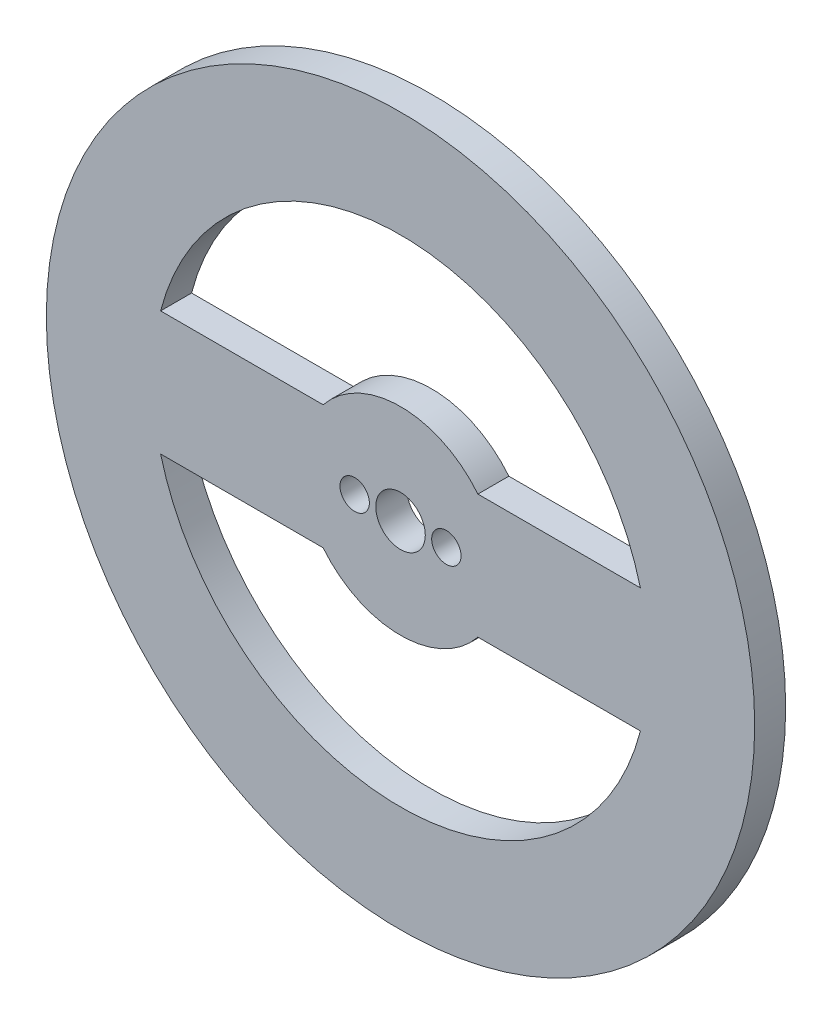
SolidWorks part; units mm, degrees
ref_plane "Front Plane" through (0, 0, 0) normal (0, 0, 1) x (1, 0, 0)
ref_plane "Top Plane" through (0, 0, 0) normal (0, 1, 0) x (1, 0, 0)
ref_plane "Right Plane" through (0, 0, 0) normal (1, 0, 0) x (0, 0, -1)
sketch "Sketch1" plane through (0, 0, 0) normal (0, 0, 1) x (1, 0, 0)
  circle A0 centre (0, 0) radius 36.3093
  dimension "D1" = 72.6186
extrude "Boss-Extrude1" add sketch "Sketch1" along normal blind 3.175
sketch "Sketch2" plane through (0, 0, 3.175) normal (0, 0, 1) x (1, 0, 0)
  line L0 (-24.5934, -6.35) -> (-7.9311, -6.35)
  line L1 (7.9311, 6.35) -> (24.5934, 6.35)
  line L2 (7.9311, -6.35) -> (24.5934, -6.35)
  line L3 (-24.5934, 6.35) -> (-7.9311, 6.35)
  line L4 (-24.5934, -6.35) -> (24.5934, 6.35) construction
  line L5 (24.5934, -6.35) -> (-24.5934, 6.35) construction
  arc A0 (7.9311, 6.35) -> (-7.9311, 6.35) centre (0, 0) ccw
  arc A1 (-24.5934, -6.35) -> (24.5934, -6.35) centre (0, 0) ccw
  arc A2 (24.5934, 6.35) -> (-24.5934, 6.35) centre (0, 0) ccw
  arc A3 (-7.9311, -6.35) -> (7.9311, -6.35) centre (0, 0) ccw
  point P9 (0, 0)
  dimension "D1" = 20.32
  dimension "D2" = 50.8
  dimension "D3" = 12.7
extrude "Cut-Extrude1" cut sketch "Sketch2" against normal through all
sketch "Sketch3" plane through (0, 0, 3.175) normal (0, 0, 1) x (1, 0, 0)
  line L0 (-36.3093, 0) -> (36.3093, 0) construction
  line L1 (7.9311, 6.35) -> (24.5934, 6.35) construction
  circle A0 centre (-4.699, 0) radius 1.505
  circle A1 centre (4.699, 0) radius 1.505
  circle A2 centre (0, 0) radius 36.3093 construction
  circle A3 centre (0, 0) radius 2.54
  point P10 (-36.3093, 0)
  point P11 (0, 0)
  dimension "D1" = 3.01
  dimension "D2" = 3.01
  dimension "D3" = 4.699
  dimension "D5" = 5.08
  dimension "D4" = 4.699
extrude "Cut-Extrude2" cut sketch "Sketch3" against normal through all
